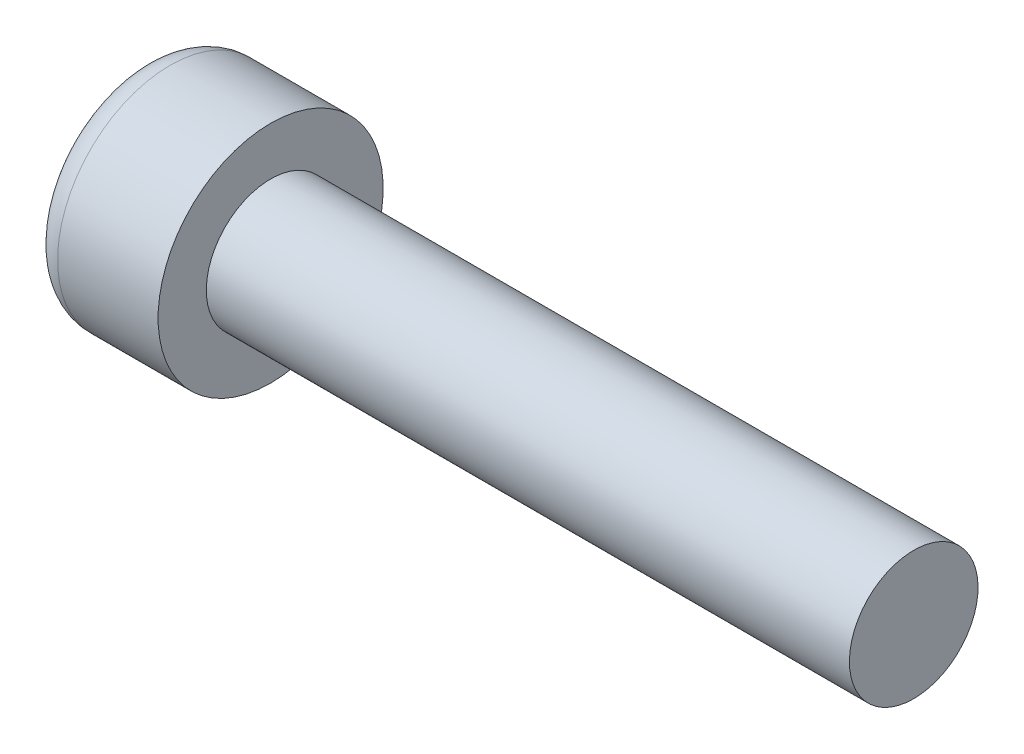
SolidWorks part; units mm, degrees
material "Plain Carbon Steel"
ref_plane "Front Plane" through (0, 0, 0) normal (0, 0, 1) x (1, 0, 0)
ref_plane "Top Plane" through (0, 0, 0) normal (0, 1, 0) x (1, 0, 0)
ref_plane "Right Plane" through (0, 0, 0) normal (1, 0, 0) x (0, 0, -1)
sketch "Sketch1" plane through (0, 0, 0) normal (0, 0, 1) x (1, 0, 0)
  line L0 (0, 0) -> (0, 2.625)
  line L1 (0.875, 3.5) -> (4, 3.5)
  line L2 (4, 3.5) -> (4, 2)
  line L3 (4, 2) -> (24, 2)
  line L4 (24, 2) -> (24, 0)
  line L5 (24, 0) -> (0, 0) construction
  line L6 (0.875, 2.625) -> (0.875, 1.75) construction
  line L7 (0.875, 1.75) -> (0.875, 0.875) construction
  line L8 (0.875, 0.875) -> (0.875, 0) construction
  line L9 (0.875, 3.5) -> (0.875, 2.625) construction
  line L10 (0, 0) -> (24, 0)
  arc A0 (0, 2.625) -> (0.875, 3.5) centre (0.875, 2.625) cw
  dimension "D1" = 4
  dimension "D2" = 7
  dimension "D3" = 4
  dimension "D4" = 20
revolve "Revolve1" add sketch "Sketch1" angle 360 about L10
sketch "Sketch2" plane through (0, 0, 0) normal (-1, 0, 0) x (0, 0, 1)
  line L1 (0, 1.7321) -> (-1.5, 0.866)
  line L2 (-1.5, 0.866) -> (-1.5, -0.866)
  line L3 (-1.5, -0.866) -> (0, -1.7321)
  line L4 (0, -1.7321) -> (1.5, -0.866)
  line L5 (1.5, -0.866) -> (1.5, 0.866)
  line L6 (1.5, 0.866) -> (0, 1.7321)
  circle A0 centre (0, 0) radius 1.5 construction
  dimension "D1" = 3
extrude "Cut-Extrude1" cut sketch "Sketch2" against normal blind 2
